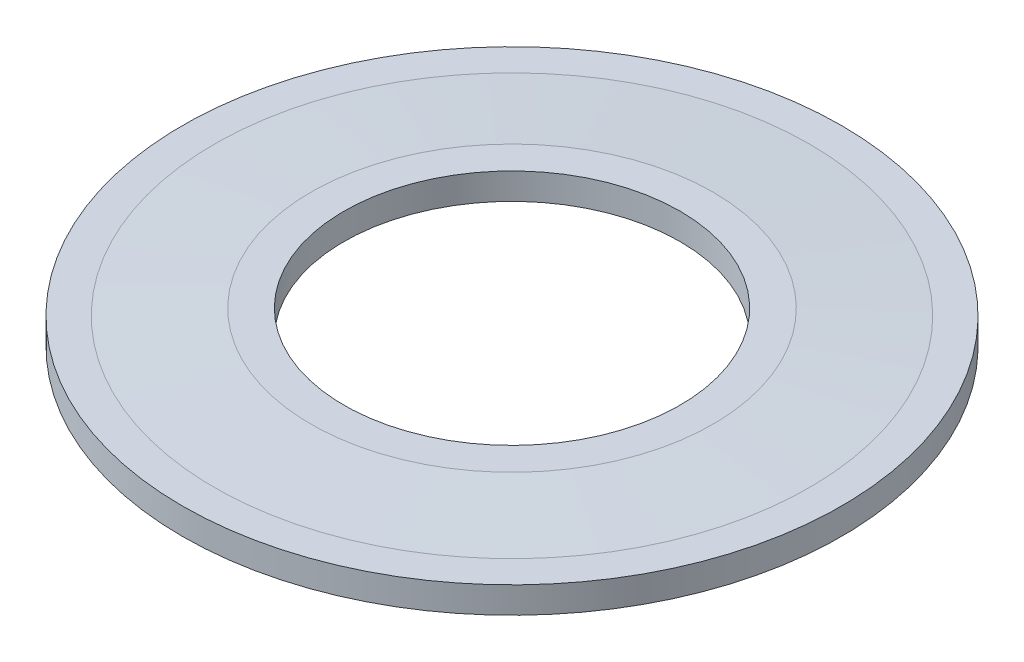
SolidWorks part; units mm, degrees
material "Rame al berillio, UNS C17000"
ref_plane "Piano frontale" through (0, 0, 0) normal (0, 0, 1) x (1, 0, 0)
ref_plane "Piano superiore" through (0, 0, 0) normal (0, 1, 0) x (1, 0, 0)
ref_plane "Piano destro" through (0, 0, 0) normal (1, 0, 0) x (0, 0, -1)
sketch "Schizzo1" plane through (0, 0, 0) normal (0, 0, 1) x (1, 0, 0)
  line L0 (0, 0) -> (0, 22.5832) construction
  line L1 (-10, 0) -> (-9, 0)
  line L2 (-9, 0) -> (-6.0727, 0.2)
  line L3 (-6.0727, 0.2) -> (-5.1, 0.2)
  line L4 (-5.1, 0.2) -> (-5.1, 1)
  line L5 (-5.1, 1) -> (-6.1, 1)
  line L6 (-6.1, 1) -> (-9.0273, 0.8)
  line L7 (-9.0273, 0.8) -> (-10, 0.8)
  line L8 (-10, 0.8) -> (-10, 0)
  dimension "D1" = 10.2
  dimension "D2" = 0.8
  dimension "D3" = 1
  dimension "D4" = 1
  dimension "D5" = 0.8
  dimension "D6" = 0.8
  dimension "D7" = 1
  dimension "D8" = 20
revolve "Rivoluzione1" add sketch "Schizzo1" angle 360 about L0
